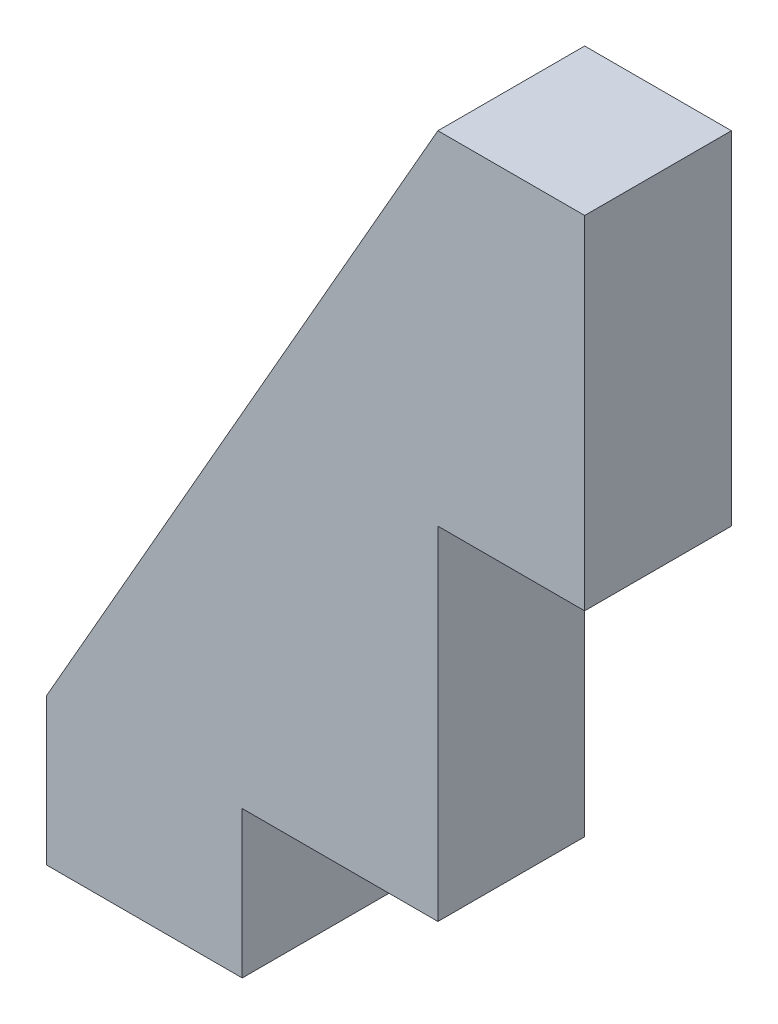
SolidWorks part; units mm, degrees
ref_plane "前视基准面" through (0, 0, 0) normal (0, 0, 1) x (1, 0, 0)
ref_plane "上视基准面" through (0, 0, 0) normal (0, 1, 0) x (1, 0, 0)
ref_plane "右视基准面" through (0, 0, 0) normal (1, 0, 0) x (0, 0, -1)
sketch "草图1" plane through (0, 0, 0) normal (0, 0, 1) x (1, 0, 0)
  line L0 (0, 0) -> (8, 0)
  line L1 (8, 0) -> (8, 14)
  line L2 (8, 14) -> (0, 0)
extrude "凸台-拉伸1" add sketch "草图1" along normal blind 3
sketch "草图2" plane through (0, 0, 0) normal (0, -1, 0) x (1, 0, 0)
  line L0 (4, 0) -> (4, 3)
  line L4 (0, 0) -> (8, 0)
  line L5 (8, 0) -> (8, 3)
  line L6 (8, 3) -> (0, 3)
  line L7 (0, 3) -> (0, 0)
  line L8 (0, 0) -> (4, 0)
  line L10 (4, 3) -> (0, 3)
  line L11 (0, 3) -> (0, 0)
  dimension "D1" = 0
extrude "凸台-拉伸2" add sketch "草图2" along normal blind 3
sketch "草图3" plane through (8, 0, 0) normal (1, 0, 0) x (0, 0, -1)
  line L0 (-3, 7) -> (0, 7)
  line L4 (0, 0) -> (0, 14)
  line L5 (0, 14) -> (-3, 14)
  line L6 (-3, 14) -> (-3, 0)
  line L7 (-3, 0) -> (0, 0)
  line L8 (0, 7) -> (0, 14)
  line L9 (0, 14) -> (-3, 14)
  line L10 (-3, 14) -> (-3, 7)
  dimension "D1" = 0
extrude "凸台-拉伸3" add sketch "草图3" along normal blind 3
